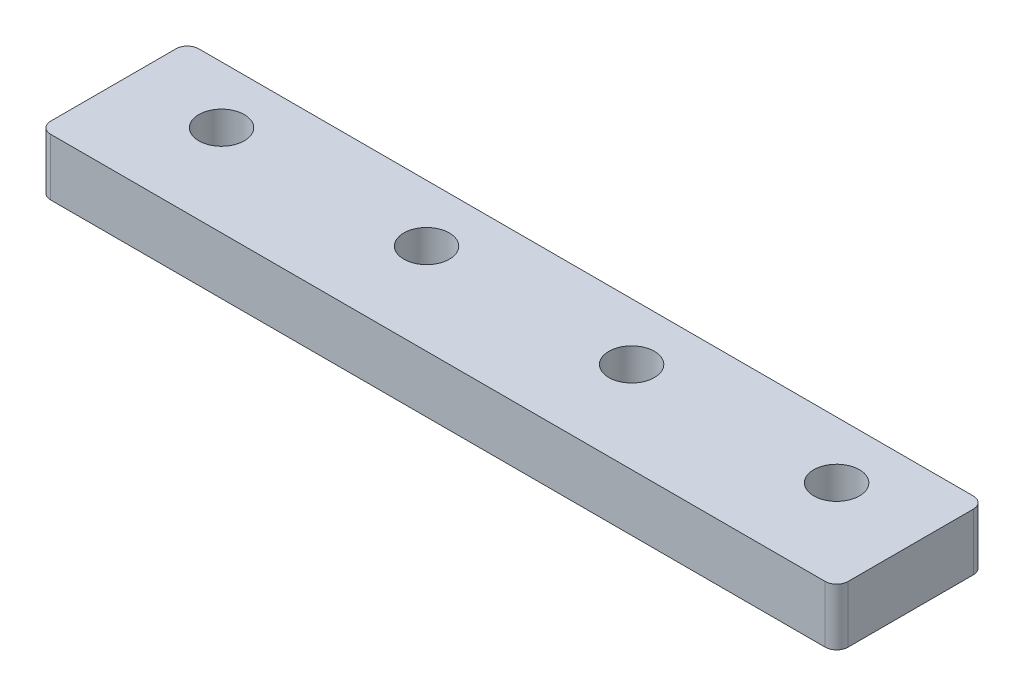
SolidWorks part; units mm, degrees
ref_plane "前视基准面" through (0, 0, 0) normal (0, 0, 1) x (1, 0, 0)
ref_plane "上视基准面" through (0, 0, 0) normal (0, 1, 0) x (1, 0, 0)
ref_plane "右视基准面" through (0, 0, 0) normal (1, 0, 0) x (0, 0, -1)
other "Configuration Table"
sketch "草图1" plane through (0, 0, 0) normal (0, 1, 0) x (1, 0, 0)
  line L0 (-27, 0) -> (-9, 0) construction
  line L1 (-35, 5) -> (35, 5)
  line L2 (-35, 5) -> (-35, -5)
  line L3 (-35, -5) -> (35, -5) construction
  line L4 (35, 5) -> (35, -5)
  line L5 (-35, 5) -> (35, -5) construction
  line L6 (-35, -5) -> (35, 5) construction
  line L7 (0, 0) -> (0, -5) construction
  line L8 (27, 0) -> (9, 0) construction
  line L9 (-35, -5) -> (-35, -8)
  line L10 (-35, -8) -> (35, -8)
  line L11 (35, -8) -> (35, -5)
  circle A0 centre (-27, 0) radius 2
  circle A1 centre (-9, 0) radius 2
  circle A2 centre (9, 0) radius 2
  circle A3 centre (27, 0) radius 2
  point P0 (0, 0)
  dimension "D4" = 4
  dimension "D1" = 70
  dimension "D2" = 10
  dimension "D3" = 18
  dimension "D5" = 18
  dimension "D6" = 3
extrude "凸台-拉伸1" add sketch "草图1" along normal blind 5
fillet "圆角1" radius 1 4 edges at (-35, 2.5, 8) (-35, 2.5, -5) (35, 2.5, -5) (35, 2.5, 8)
